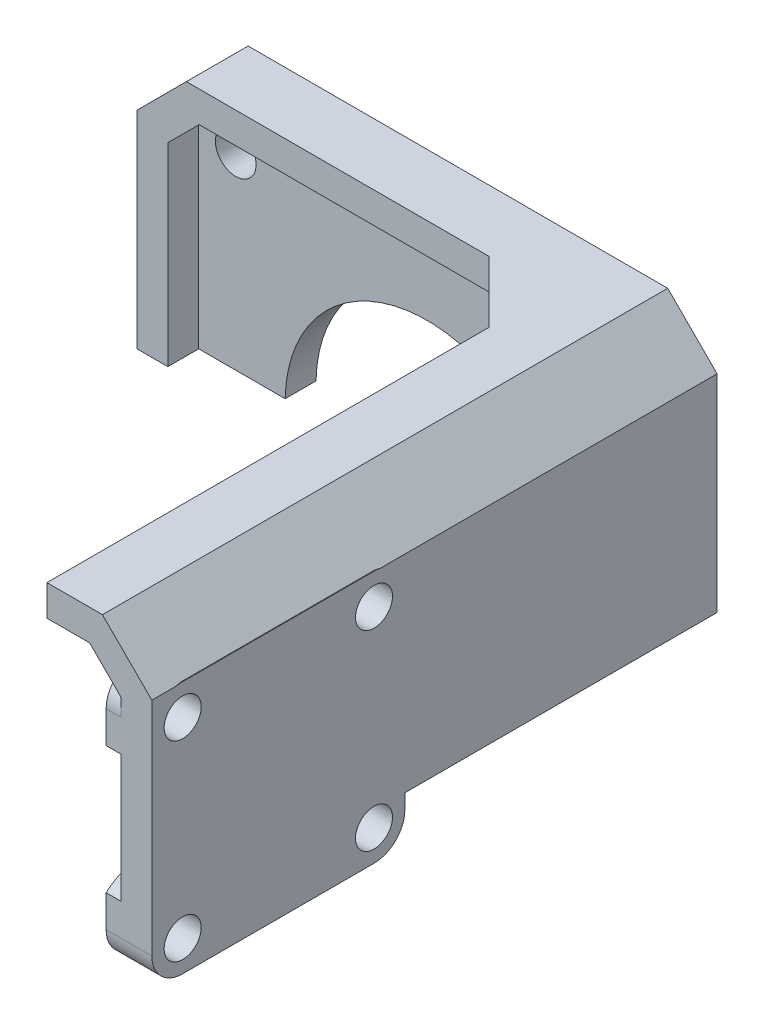
SolidWorks part; units mm, degrees
ref_plane "Front Plane" through (0, 0, 0) normal (0, 0, 1) x (1, 0, 0)
ref_plane "Top Plane" through (0, 0, 0) normal (0, 1, 0) x (1, 0, 0)
ref_plane "Right Plane" through (0, 0, 0) normal (1, 0, 0) x (0, 0, -1)
sketch "Sketch1" plane through (0, 0, 0) normal (0, 0, 1) x (1, 0, 0)
  line L0 (-21, 0.25) -> (21, 0.25)
  line L1 (-21, 21) -> (21, 21) construction
  line L2 (-21, 21) -> (-21, -21) construction
  line L3 (-21, -21) -> (21, -21) construction
  line L4 (21, 21) -> (21, -21) construction
  line L5 (-21, 21) -> (21, -21) construction
  line L6 (-21, -21) -> (21, 21) construction
  line L7 (21, 0.25) -> (21, 17)
  line L8 (21, 17) -> (17, 21)
  line L9 (17, 21) -> (-17, 21)
  line L10 (-17, 21) -> (-21, 17)
  line L11 (-21, 17) -> (-21, 0.25)
  point P0 (0, 0)
  dimension "D1" = 42
  dimension "D2" = 4
  dimension "D3" = 4
  dimension "D4" = 0.25
extrude "Boss-Extrude1" add sketch "Sketch1" along normal blind 2.5
sketch "Sketch2" plane through (0, 0, 2.5) normal (0, 0, 1) x (1, 0, 0)
  arc A0 (-11.4973, -0.25) -> (11.4973, -0.25) centre (0, 0) ccw construction
  arc A1 (-11.4973, -0.25) -> (11.4973, -0.25) centre (0, 0) ccw construction
  circle A2 centre (0, 0) radius 11.5
extrude "Cut-Extrude1" cut sketch "Sketch2" against normal blind 3
sketch "Sketch3" plane through (0, 0, 0) normal (0, 0, -1) x (-1, 0, 0)
  circle A0 centre (15.5, 15.5) radius 1.65
  circle A1 centre (-15.5, 15.5) radius 1.65
  point P0 (15.5, 15.5)
  point P1 (-15.5, 15.5)
  dimension "D1" = 3.3
extrude "Cut-Extrude2" cut sketch "Sketch3" against normal blind 3
sketch "Sketch4" plane through (0, 0, 2.5) normal (0, 0, 1) x (1, 0, 0)
  line L0 (21, 0.25) -> (21, 17) construction
  line L1 (21, 17) -> (17, 21) construction
  line L2 (17, 21) -> (-17, 21) construction
  line L3 (-17, 21) -> (-21, 17) construction
  line L4 (-21, 17) -> (-21, 0.25) construction
  line L5 (21, 0.25) -> (21, 17)
  line L6 (21, 17) -> (17, 21)
  line L7 (17, 21) -> (-17, 21)
  line L8 (-17, 21) -> (-21, 17)
  line L9 (-21, 17) -> (-21, 0.25)
extrude "Extrude-Thin1" add sketch "Sketch4" along normal up to vertex (43.3 mm away) thin thin type one direction reverse wall 2.5
sketch "Sketch6" plane through (21, 0, 0) normal (1, 0, 0) x (0, 0, -1)
  line L4 (-45.8, 14.55) -> (-45.8, -0.95)
  line L5 (-43.3, -3.45) -> (-27.8, -3.45)
  line L6 (-25.3, -0.95) -> (-25.3, 14.55)
  line L7 (-27.8, 17.05) -> (-43.3, 17.05)
  line L8 (-45.8, 14.55) -> (-45.8, -0.95)
  line L9 (-43.3, -3.45) -> (-27.8, -3.45)
  line L10 (-25.3, -0.95) -> (-25.3, 14.55)
  line L11 (-27.8, 17.05) -> (-43.3, 17.05)
  arc A4 (-43.3, 17.05) -> (-45.8, 14.55) centre (-43.3, 14.55) ccw
  arc A5 (-45.8, -0.95) -> (-43.3, -3.45) centre (-43.3, -0.95) ccw
  arc A6 (-27.8, -3.45) -> (-25.3, -0.95) centre (-27.8, -0.95) ccw
  arc A7 (-25.3, 14.55) -> (-27.8, 17.05) centre (-27.8, 14.55) ccw
  arc A8 (-43.3, 17.05) -> (-45.8, 14.55) centre (-43.3, 14.55) ccw
  arc A9 (-45.8, -0.95) -> (-43.3, -3.45) centre (-43.3, -0.95) ccw
  arc A10 (-27.8, -3.45) -> (-25.3, -0.95) centre (-27.8, -0.95) ccw
  arc A11 (-25.3, 14.55) -> (-27.8, 17.05) centre (-27.8, 14.55) ccw
  dimension "D1" = 0
extrude "Boss-Extrude2" add sketch "Sketch6" against normal blind 2.5
sketch "Sketch7" plane through (0, 21, 0) normal (0, 1, 0) x (1, 0, 0)
  line L2 (-12.5, -5) -> (12.5, -5) construction
  line L3 (-12.5, -5) -> (-12.5, -45.8) construction
  line L4 (-12.5, -45.8) -> (12.5, -45.8) construction
  line L5 (12.5, -5) -> (12.5, -45.8) construction
  line L6 (-12.5, -5) -> (12.5, -45.8) construction
  line L7 (-12.5, -45.8) -> (12.5, -5) construction
  line L9 (17, -45.8) -> (-17, -45.8) construction
  line L10 (17, 0) -> (-17, 0) construction
  line L12 (12.5, -5) -> (-21, -5)
  line L13 (12.5, -5) -> (12.5, -45.8)
  line L14 (12.5, -45.8) -> (-21, -45.8)
  line L15 (-21, -5) -> (-21, -45.8)
  point P2 (0, -25.4)
  dimension "D1" = 25
  dimension "D2" = 5
  dimension "D3" = 8.5
extrude "Cut-Extrude3" cut sketch "Sketch7" against normal through all both and the other way through all
chamfer "Chamfer1" distance 5 angle 45 1 edges at (12.5, 19.75, 5)
sketch "Sketch8" plane through (18.5, 0, 0) normal (-1, 0, 0) x (0, 0, 1)
  line L0 (27.8, -3.45) -> (43.3, -3.45) construction
  line L1 (45.8, -0.95) -> (45.8, 14.55) construction
  line L2 (43.3, 17.05) -> (27.8, 17.05) construction
  line L3 (25.3, 14.55) -> (25.3, -0.95) construction
  line L4 (27.8, -3.45) -> (30.3904, -3.45)
  line L5 (45.8, -0.95) -> (45.8, 1.6404)
  line L6 (43.3, 17.05) -> (40.7096, 17.05)
  line L7 (25.3, 14.55) -> (25.3, 11.9596)
  line L8 (25.3, 1.6404) -> (25.3, -0.95)
  line L9 (30.3904, 17.05) -> (27.8, 17.05)
  line L10 (45.8, 11.9596) -> (45.8, 14.55)
  line L11 (40.7096, -3.45) -> (43.3, -3.45)
  circle A0 centre (27.8, 14.55) radius 1.6 construction
  circle A1 centre (43.3, 14.55) radius 1.6 construction
  circle A2 centre (27.8, 14.55) radius 1.6 construction
  circle A3 centre (43.3, 14.55) radius 1.6 construction
  arc A4 (25.3, 11.9596) -> (30.3904, 17.05) centre (27.8, 14.55) ccw
  arc A5 (40.7096, 17.05) -> (45.8, 11.9596) centre (43.3, 14.55) ccw
  circle A6 centre (27.8, -0.95) radius 1.6 construction
  circle A7 centre (43.3, -0.95) radius 1.6 construction
  circle A8 centre (27.8, -0.95) radius 1.6 construction
  circle A9 centre (43.3, -0.95) radius 1.6 construction
  arc A10 (30.3904, -3.45) -> (25.3, 1.6404) centre (27.8, -0.95) ccw
  arc A11 (45.8, 1.6404) -> (40.7096, -3.45) centre (43.3, -0.95) ccw
  arc A12 (43.3, -3.45) -> (45.8, -0.95) centre (43.3, -0.95) ccw construction
  arc A13 (25.3, -0.95) -> (27.8, -3.45) centre (27.8, -0.95) ccw construction
  arc A14 (45.8, 14.55) -> (43.3, 17.05) centre (43.3, 14.55) ccw construction
  arc A15 (27.8, 17.05) -> (25.3, 14.55) centre (27.8, 14.55) ccw construction
  arc A16 (43.3, -3.45) -> (45.8, -0.95) centre (43.3, -0.95) ccw
  arc A17 (25.3, -0.95) -> (27.8, -3.45) centre (27.8, -0.95) ccw
  arc A18 (45.8, 14.55) -> (43.3, 17.05) centre (43.3, 14.55) ccw
  arc A19 (27.8, 17.05) -> (25.3, 14.55) centre (27.8, 14.55) ccw
  circle A20 centre (27.8, 14.55) radius 3.6 construction
  circle A21 centre (43.3, 14.55) radius 3.6 construction
  circle A22 centre (27.8, -0.95) radius 3.6 construction
  circle A23 centre (43.3, -0.95) radius 3.6 construction
  dimension "D1" = 2
  dimension "D2" = 2
extrude "Boss-Extrude3" add sketch "Sketch8" along normal up to vertex (1.2 mm away)
sketch "Sketch10" plane through (17.3, 0, 0) normal (-1, 0, 0) x (0, 0, 1)
  circle A0 centre (43.3, 14.55) radius 1.5
  circle A1 centre (27.8, 14.55) radius 1.5
  circle A2 centre (27.8, -0.95) radius 1.5
  circle A3 centre (43.3, -0.95) radius 1.5
  dimension "D1" = 3
extrude "Cut-Extrude4" cut sketch "Sketch10" against normal blind 10
ref_plane "Plane1" through (0, 0, 19.3) normal (0, 0, -1) x (-1, 0, 0)
sketch "Sketch12" plane through (0, 0.25, 0) normal (0, -1, 0) x (1, 0, 0)
  line L0 (11.4973, 2.5) -> (11.4973, 0) construction
  line L1 (21, 0) -> (11.4973, 0)
  line L2 (21, 0) -> (21, 19.3)
  line L3 (21, 19.3) -> (11.4973, 19.3)
  line L4 (11.4973, 0) -> (11.4973, 19.3)
  line L5 (17.3, 25.3) -> (21, 25.3) construction
  dimension "D1" = 6
extrude "Boss-Extrude4" add sketch "Sketch12" against normal blind 5
sketch "Sketch13" plane through (0, 5.25, 0) normal (0, 1, 0) x (1, 0, 0)
  circle A0 centre (14.9986, -15.8) radius 1.65 construction
  circle A1 centre (14.9986, -15.8) radius 1.65 construction
  circle A2 centre (14.9986, -15.8) radius 1.5
  dimension "D1" = 3
extrude "Cut-Extrude5" cut sketch "Sketch13" against normal through all
